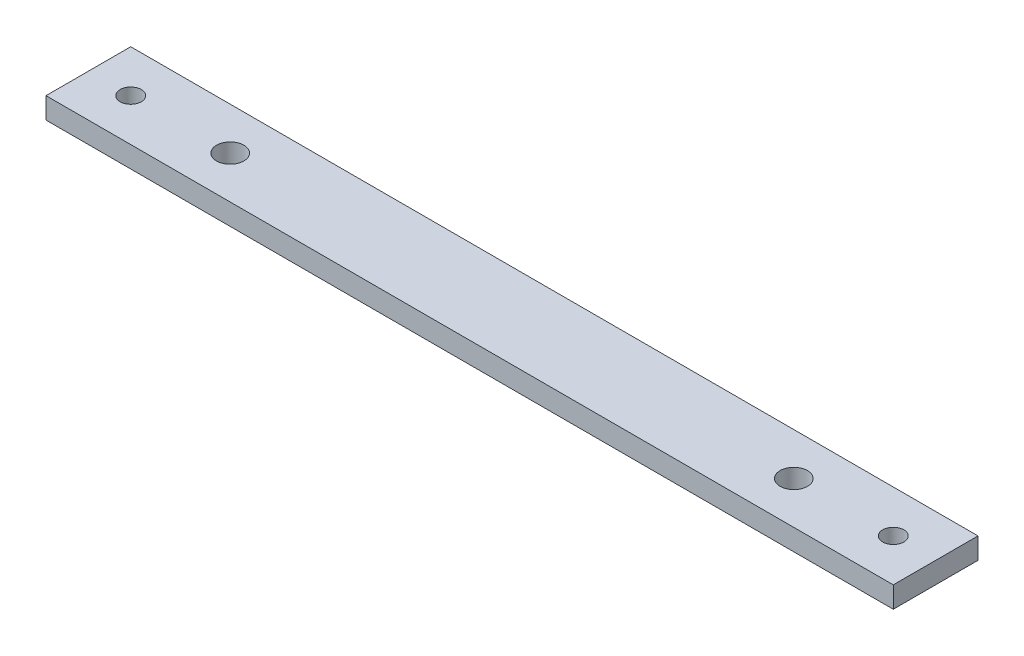
SolidWorks part; units mm, degrees
material "6061 Alloy"
ref_plane "Front Plane" through (0, 0, 0) normal (0, 0, 1) x (1, 0, 0)
ref_plane "Top Plane" through (0, 0, 0) normal (0, 1, 0) x (1, 0, 0)
ref_plane "Right Plane" through (0, 0, 0) normal (1, 0, 0) x (0, 0, -1)
sketch "Sketch1" plane through (0, 0, 0) normal (0, 1, 0) x (1, 0, 0)
  line L1 (0, 0) -> (-254, 0)
  line L2 (0, 0) -> (0, 25.4)
  line L3 (0, 25.4) -> (-254, 25.4)
  line L4 (-254, 0) -> (-254, 25.4)
  dimension "D2" = 25.4
  dimension "D1" = 254
extrude "Boss-Extrude1" add sketch "Sketch1" along normal blind 6.35
sketch "Sketch2" plane through (0, 6.35, 0) normal (0, 1, 0) x (1, 0, 0)
  line L0 (-127, 12.7) -> (-127, 25.4) construction
  line L1 (0, 25.4) -> (-254, 25.4) construction
  line L2 (-127, 12.7) -> (-127, 0) construction
  line L3 (-254, 0) -> (0, 0) construction
  circle A0 centre (-127, 12.7) radius 5.08
  dimension "D1" = 10.16
extrude "1/2-20 thread thru" [suppressed] cut sketch "Sketch2" against normal through all
sketch "Sketch3" plane through (0, 0, 0) normal (0, -1, 0) x (1, 0, 0)
  line L0 (-254, -12.7) -> (-215.9635, -12.7) construction
  line L1 (-254, -25.4) -> (-254, 0) construction
  line L2 (-254, -12.7) -> (-198.0565, -12.7) construction
  line L3 (0, -12.7) -> (-38.0365, -12.7) construction
  line L4 (0, 0) -> (0, -25.4) construction
  line L5 (0, -12.7) -> (-55.9435, -12.7) construction
  circle A0 centre (-38.0365, -12.7) radius 2.0193
  circle A1 centre (-55.9435, -12.7) radius 2.0193
  circle A2 centre (-215.9635, -12.7) radius 2.0193
  circle A3 centre (-198.0565, -12.7) radius 2.0193
  dimension "D3" = 4.0386
  dimension "D1" = 38.0365
  dimension "D2" = 55.9435
extrude "Cut-Extrude3" [suppressed] cut sketch "Sketch3" against normal blind 10.16
sketch "Sketch4" plane through (0, 0, 0) normal (0, -1, 0) x (1, 0, 0)
  line L2 (0, 0) -> (0, -25.4) construction
  line L3 (-254, -25.4) -> (-254, 0) construction
  circle A0 centre (-211.4804, -12.7) radius 4.1021
  circle A1 centre (-42.5196, -12.7) radius 4.1021
  dimension "D2" = 8.2042
  dimension "D1" = 42.5196
  dimension "D3" = 42.5196
extrude "Cut-Extrude4" cut sketch "Sketch4" against normal through all
hole_wizard "1/4 (0.25) Diameter Hole1" positions "Sketch6" profile "Sketch7" hole size "1/4" standard "ANSI Inch" end condition through all
sketch "Sketch6" plane through (0, 0, 0) normal (0, -1, 0) x (-1, 0, 0)
  line L0 (254, 25.4) -> (254, 0) construction
  line L2 (0, 25.4) -> (254, 25.4) construction
  line L3 (254, 0) -> (0, 0) construction
  line L4 (0, 0) -> (0, 25.4) construction
  point P0 (241.3, 12.7)
  point P3 (12.7, 12.7)
  dimension "D1" = 12.7
  dimension "D2" = 12.7
  dimension "D3" = 12.7
  dimension "D4" = 12.7
sketch "Sketch7" plane through (-241.3, 0, -12.7) normal (1, 0, 0) x (0, 0, -1)
  line L0 (0, 0) -> (0, 6.35)
  line L1 (0, 6.35) -> (3.175, 6.35)
  line L2 (3.175, 6.35) -> (3.175, 0)
  line L5 (3.175, 0) -> (0, 0)
  line L11 (0, -6.35) -> (0, 107.95) construction
  dimension "Thru Hole Dia." = 6.35
  dimension "Thru Hole Depth" = 6.35
hole_wizard "1/2-20 Tapped Hole3" positions "Sketch14" profile "Sketch15" tap size "1/2-20" standard "ANSI Inch"
sketch "Sketch14" [suppressed] plane through (0, 12.7, 0) normal (0, 1, 0) x (1, 0, 0)
  point P0 (-127, 12.7)
sketch "Sketch15" plane through (-127, 12.7, -12.7) normal (1, 0, 0) x (0, 0, 1)
  line L0 (0, 0) -> (0, 12.7)
  line L1 (0, 12.7) -> (5.7544, 12.7)
  line L2 (5.7544, 12.7) -> (5.7544, 0)
  line L5 (5.7544, 0) -> (0, 0)
  line L11 (0, -6.35) -> (0, 107.95) construction
  dimension "Thru Tap Drill Dia." = 11.5087
  dimension "Thru Tap Drill Depth" = 12.7
cosmetic thread "Hole Thread1"
sketch3d "Sketch_MAC1-1_TOPBEAM_MILLING" [suppressed]
  line L0 (-254, 0, -25.4) -> (-244, 0, -25.4)
  line L1 (-254, 0, -25.4) -> (-254, 0, -15.4)
  point P0 (-254, 0, -25.4)
  point P1 (-244, 0, -25.4)
  point P2 (-254, 0, -15.4)
sketch3d "Stock_TOPBEAM_MILLING"
  line L0 (-254, 12.7, -25.4) -> (0, 12.7, -25.4)
  line L1 (0, 12.7, -25.4) -> (0, 12.7, 0)
  line L2 (0, 12.7, 0) -> (-254, 12.7, 0)
  line L3 (-254, 12.7, 0) -> (-254, 12.7, -25.4)
  line L4 (-254, 0, -25.4) -> (0, 0, -25.4)
  line L5 (0, 0, -25.4) -> (0, 0, 0)
  line L6 (0, 0, 0) -> (-254, 0, 0)
  line L7 (-254, 0, 0) -> (-254, 0, -25.4)
  line L8 (-254, 12.7, -25.4) -> (-254, 0, -25.4)
  line L9 (0, 12.7, -25.4) -> (0, 0, -25.4)
  line L10 (0, 12.7, 0) -> (0, 0, 0)
  line L11 (-254, 12.7, 0) -> (-254, 0, 0)
  point P8 (-127, 12.7, -25.4)
  point P9 (0, 12.7, -12.7)
  point P10 (-127, 12.7, 0)
  point P11 (-254, 12.7, -12.7)
  point P12 (-127, 0, -25.4)
  point P13 (0, 0, -12.7)
  point P14 (-127, 0, 0)
  point P15 (-254, 0, -12.7)
  point P16 (-254, 6.35, -25.4)
  point P17 (0, 6.35, -25.4)
  point P18 (0, 6.35, 0)
  point P19 (-254, 6.35, 0)
  point P20 (-127, 6.35, -12.7)
  point P21 (-127, 6.35, -25.4)
  point P22 (-127, 0, -12.7)
  point P23 (-127, 6.35, 0)
  point P24 (-127, 12.7, -12.7)
  point P25 (-254, 6.35, -12.7)
  point P26 (0, 6.35, -12.7)
equation "\"cross_length\"=10"
equation "\"wing_spar_height\"= 2"
equation "\"wing_spar_thickness\"= .5"
equation "\"frame_width\"= 10"
equation "\"D1@Sketch1\"=\"frame_width\""
